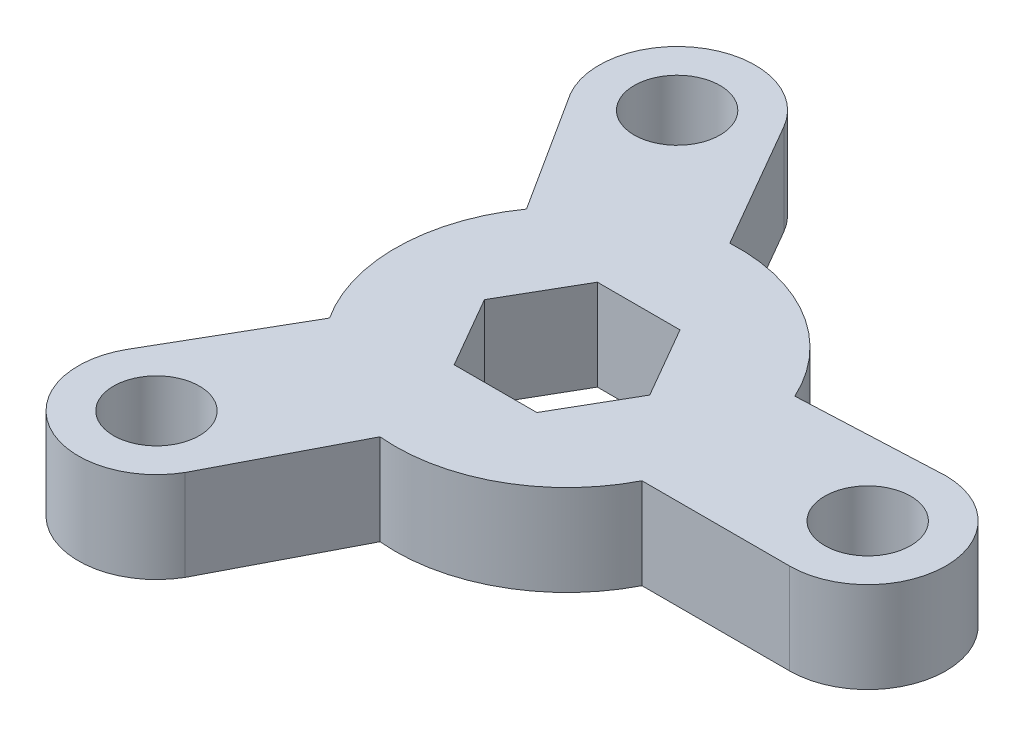
SolidWorks part; units mm, degrees
ref_plane "Front" through (0, 0, 0) normal (0, 0, 1) x (1, 0, 0)
ref_plane "Top" through (0, 0, 0) normal (0, 1, 0) x (1, 0, 0)
ref_plane "Right" through (0, 0, 0) normal (1, 0, 0) x (0, 0, -1)
sketch "Sketch1" plane through (0, 0, 0) normal (0, 1, 0) x (1, 0, 0)
  line L0 (2.5148, 0.2447) -> (13.0148, 0.2447)
  line L1 (2.5148, 0.2447) -> (-2.7352, 9.338)
  line L2 (2.5148, 0.2447) -> (-2.7352, -8.8486)
  line L3 (2.5148, 0.2447) -> (-2.7352, 9.338) construction
  line L4 (5.4015, 0.2447) -> (3.9581, 2.7447)
  line L5 (3.9581, 2.7447) -> (1.0714, 2.7447)
  line L6 (1.0714, 2.7447) -> (-0.372, 0.2447)
  line L7 (-0.372, 0.2447) -> (1.0714, -2.2553)
  line L8 (1.0714, -2.2553) -> (3.9581, -2.2553)
  line L9 (3.9581, -2.2553) -> (5.4015, 0.2447)
  line L10 (2.5148, 0.2447) -> (13.0148, 0.2447) construction
  line L11 (13.0148, -2.4841) -> (7.8583, -2.4841)
  line L12 (13.0148, 2.9736) -> (7.9691, 2.7447)
  line L13 (-5.0985, -7.4841) -> (-2.5203, -3.0185)
  line L14 (-0.372, -10.213) -> (1.9526, -5.7289)
  line L15 (-0.372, 10.7024) -> (2.2062, 6.2368)
  line L16 (-5.0985, 7.9736) -> (-2.3775, 3.7183)
  circle A0 centre (-2.7352, 9.338) radius 1.5
  circle A1 centre (13.0148, 0.2447) radius 1.5
  circle A2 centre (-2.7352, -8.8486) radius 1.5
  circle A3 centre (2.5148, 0.2447) radius 2.5 construction
  arc A4 (-0.372, 10.7024) -> (-5.0985, 7.9736) centre (-2.7352, 9.338) ccw
  circle A5 centre (2.5148, 0.2447) radius 6
  arc A6 (13.0148, -2.4841) -> (13.0148, 2.9736) centre (13.0148, 0.2447) ccw
  arc A7 (-5.0985, -7.4841) -> (-0.372, -10.213) centre (-2.7352, -8.8486) ccw
  point P39 (2.5148, 0.2447)
  dimension "D1" = 3
  dimension "D2" = 120
  dimension "D3" = 3
extrude "Boss-Extrude1" add sketch "Sketch1" along normal blind 3.175
